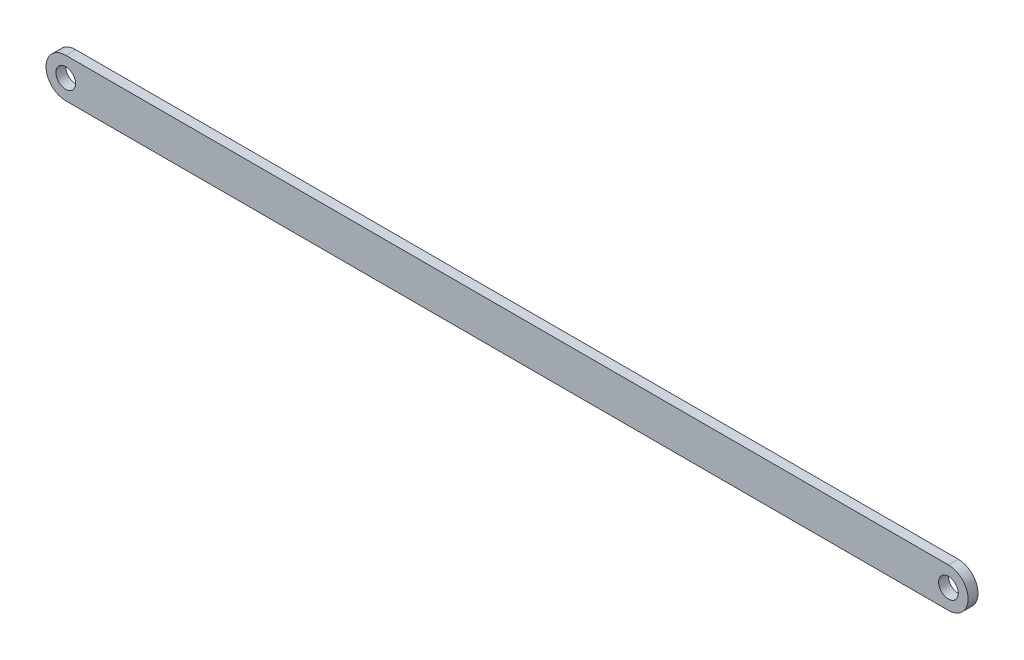
SolidWorks part; units mm, degrees
ref_plane "Plano frontal" through (0, 0, 0) normal (0, 0, 1) x (1, 0, 0)
ref_plane "Plano superior" through (0, 0, 0) normal (0, 1, 0) x (1, 0, 0)
ref_plane "Plano direito" through (0, 0, 0) normal (1, 0, 0) x (0, 0, -1)
sketch "Esboço1" plane through (0, 0, 0) normal (0, 0, 1) x (1, 0, 0)
  line L0 (-44.785, 2) -> (44.785, 2)
  line L1 (-5.0073, 0) -> (5.0073, 0) construction
  line L2 (-44.785, -2) -> (44.785, -2)
  arc A0 (-44.785, 2) -> (-44.785, -2) centre (-44.785, 0) ccw
  arc A1 (44.785, 2) -> (44.785, -2) centre (44.785, 0) cw
  circle A2 centre (-44.785, 0) radius 1
  circle A3 centre (44.785, 0) radius 1
  point P3 (0, 2)
  dimension "D1" = 2
  dimension "D2" = 89.57
extrude "Ressalto-extrusão1" add sketch "Esboço1" along normal blind 1
